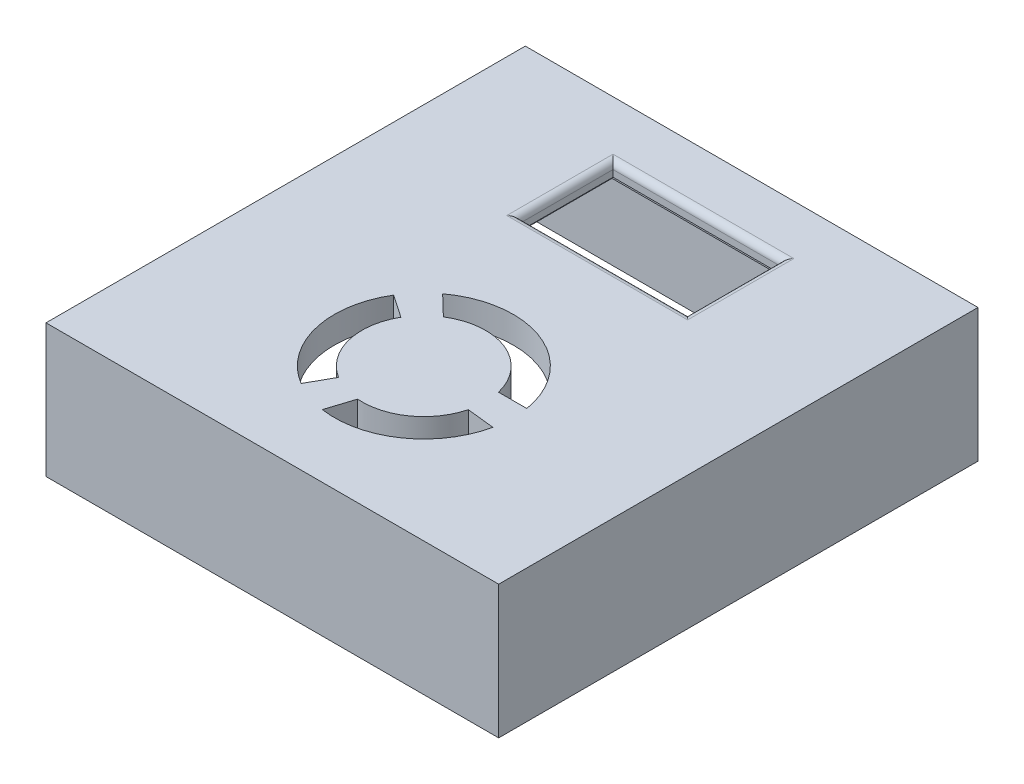
SolidWorks part; units mm, degrees
ref_plane "前视基准面" through (0, 0, 0) normal (0, 0, 1) x (1, 0, 0)
ref_plane "上视基准面" through (0, 0, 0) normal (0, 1, 0) x (1, 0, 0)
ref_plane "右视基准面" through (0, 0, 0) normal (1, 0, 0) x (0, 0, -1)
sketch "草图1" plane through (0, 0, 0) normal (0, 1, 0) x (1, 0, 0)
  line L1 (-17, -18) -> (17, -18)
  line L2 (-17, -18) -> (-17, 18)
  line L3 (-17, 18) -> (17, 18)
  line L4 (17, -18) -> (17, 18)
  line L5 (-17, -18) -> (17, 18) construction
  line L6 (-17, 18) -> (17, -18) construction
  point P0 (0, 0)
extrude "凸台-拉伸1" add sketch "草图1" along normal blind 10
shell "抽壳1" thickness 1
sketch "草图2" plane through (0, 0, 0) normal (0, 1, 0) x (1, 0, 0)
  line L1 (-6.1757, 6.7844) -> (6.4043, 6.7844)
  line L2 (-6.1757, 6.7844) -> (-6.1757, 13.7644)
  line L3 (-6.1757, 13.7644) -> (6.4043, 13.7644)
  line L4 (6.4043, 6.7844) -> (6.4043, 13.7644)
  line L5 (-6.1757, 6.7844) -> (6.4043, 13.7644) construction
  line L6 (-6.1757, 13.7644) -> (6.4043, 6.7844) construction
extrude "切除-拉伸1" cut sketch "草图2" against normal mid plane 10.001 from surface at 8 contours L4 L3 L2 L1 starting at face at (0, 8, 0)
sketch "草图6" plane through (0, 0, 0) normal (0, 1, 0) x (1, 0, 0)
  line L1 (7.5621, 14.6513) -> (-7.1379, 14.6513)
  line L2 (7.5621, 14.6513) -> (7.5621, 2.8513)
  line L3 (7.5621, 2.8513) -> (-7.1379, 2.8513)
  line L4 (-7.1379, 14.6513) -> (-7.1379, 2.8513)
extrude "切除-拉伸2" cut sketch "草图6" against normal mid plane 2 from surface at 8 starting at face at (0, 8, 0)
fillet "圆角2" radius 0.5 4 edges at (0.1143, 10, -6.7844) (6.4043, 10, -10.2744) (0.1143, 10, -13.7644) (-6.1757, 10, -10.2744)
sketch "草图10" plane through (0, 0, 0) normal (0, 1, 0) x (1, 0, 0)
  line L0 (-3.9937, -1.2153) -> (-2.4638, -2.6904)
  line L1 (-5.7502, -3.1423) -> (-4.0353, -4.3091)
  line L2 (-3.4775, -12.37) -> (-2.4643, -10.5631)
  line L3 (-0.3376, -11.2645) -> (-0.9797, -13.268)
  line L4 (4.5055, -5.5199) -> (6.6287, -5.5159)
  line L5 (6.5735, -8.0153) -> (4.5081, -7.7879)
  arc A1 (-5.7502, -3.1423) -> (-3.4775, -12.37) centre (0, -6.6198) ccw
  arc A2 (-0.9797, -13.268) -> (6.5735, -8.0153) centre (0, -6.6198) ccw
  arc A3 (6.6287, -5.5159) -> (-3.9937, -1.2153) centre (0, -6.6198) ccw
  arc A4 (-2.4638, -2.6904) -> (4.5055, -5.5199) centre (0, -6.6198) cw
  arc A5 (-0.3376, -11.2645) -> (4.5081, -7.7879) centre (0, -6.6198) ccw
  arc A6 (-4.0353, -4.3091) -> (-2.4643, -10.5631) centre (0, -6.6198) ccw
extrude "切除-拉伸3" cut sketch "草图10" against normal blind 2 from surface at 10 starting at face at (0.1143, 10, -10.2744)
sketch "草图11" plane through (0, 0, 0) normal (1, 0, 0) x (0, 0, -1)
  line L0 (13.1654, 7.7635) -> (12.6154, 7.7635)
  line L1 (15.8555, 7.7458) -> (15.3055, 7.7458)
  line L2 (16.3555, 7.2458) -> (16.3555, 2.6458)
  line L3 (15.8555, 2.1458) -> (15.3055, 2.1458)
  line L4 (14.8055, 7.2458) -> (14.8055, 2.6458)
  line L5 (13.6654, 7.2635) -> (13.6654, 2.6635)
  line L6 (13.1654, 2.1635) -> (12.6154, 2.1635)
  line L7 (12.1154, 7.2635) -> (12.1154, 2.6635)
  line L8 (10.5246, 7.7634) -> (9.9746, 7.7634)
  line L9 (11.0246, 7.2634) -> (11.0246, 2.6634)
  line L10 (10.5246, 2.1634) -> (9.9746, 2.1634)
  line L11 (9.4746, 7.2634) -> (9.4746, 2.6634)
  arc A0 (13.1654, 7.7635) -> (13.6654, 7.2635) centre (13.1654, 7.2635) cw
  arc A1 (12.6154, 7.7635) -> (12.1154, 7.2635) centre (12.6154, 7.2635) ccw
  arc A2 (10.5246, 7.7634) -> (11.0246, 7.2634) centre (10.5246, 7.2634) cw
  arc A3 (9.9746, 7.7634) -> (9.4746, 7.2634) centre (9.9746, 7.2634) ccw
  arc A4 (9.9746, 2.1634) -> (9.4746, 2.6634) centre (9.9746, 2.6634) cw
  arc A5 (11.0246, 2.6634) -> (10.5246, 2.1634) centre (10.5246, 2.6634) cw
  arc A6 (12.6154, 2.1635) -> (12.1154, 2.6635) centre (12.6154, 2.6635) cw
  arc A7 (13.6654, 2.6635) -> (13.1654, 2.1635) centre (13.1654, 2.6635) cw
  arc A8 (15.3055, 2.1458) -> (14.8055, 2.6458) centre (15.3055, 2.6458) cw
  arc A9 (16.3555, 2.6458) -> (15.8555, 2.1458) centre (15.8555, 2.6458) cw
  arc A10 (15.3055, 7.7458) -> (14.8055, 7.2458) centre (15.3055, 7.2458) ccw
  arc A11 (15.8555, 7.7458) -> (16.3555, 7.2458) centre (15.8555, 7.2458) cw
  dimension "D1" = 0.5
extrude "切除-拉伸4" cut sketch "草图11" against normal blind 1 from surface at -16 starting at face at (-16, 4, 0)
sketch "草图13" plane through (0, 0, 0) normal (0, 0, 1) x (1, 0, 0)
  line L1 (5.0366, 1.5) -> (14.23, 1.5)
  line L2 (5.0366, 1.5) -> (5.0366, 0)
  line L3 (5.0366, 0) -> (14.23, 0)
  line L4 (14.23, 1.5) -> (14.23, 0)
extrude "切除-拉伸5" cut sketch "草图13" along normal blind 0.5 from surface at 17 starting at face at (0, 4, 17)
